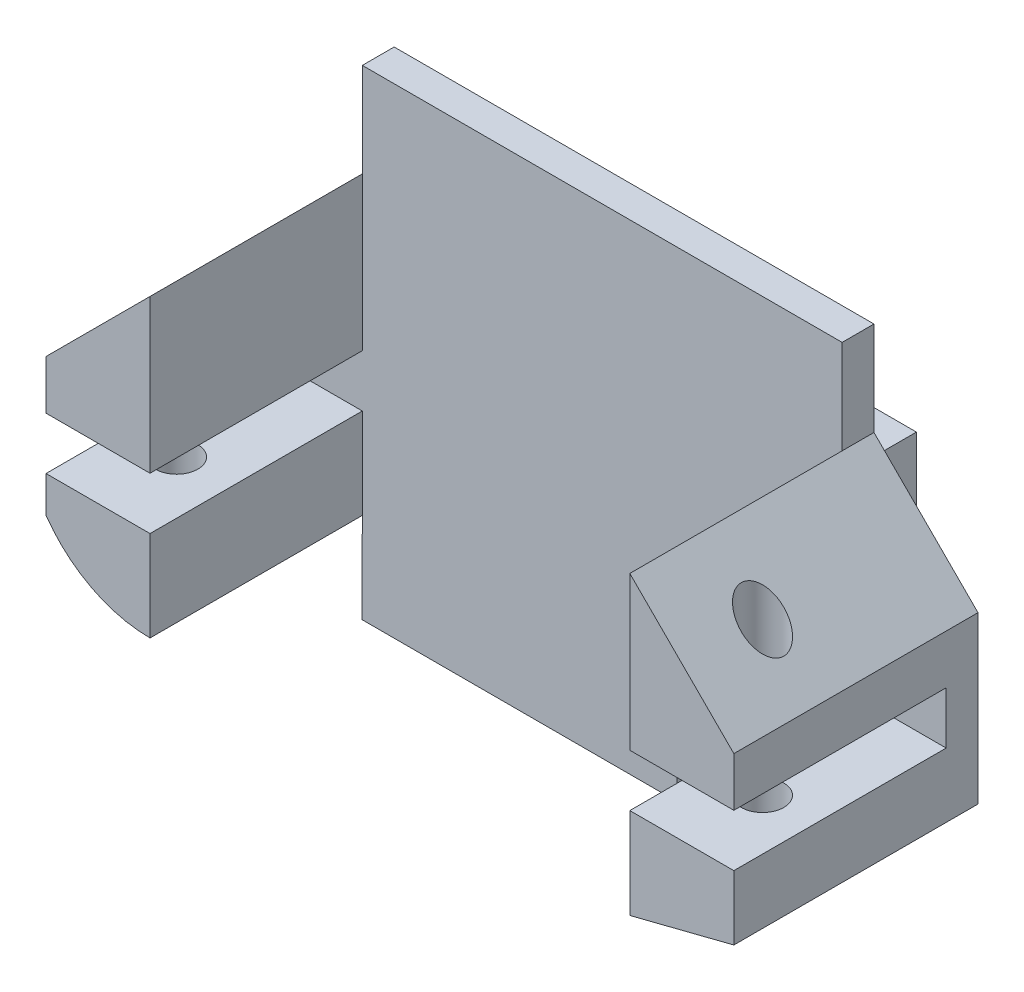
SolidWorks part; units mm, degrees
ref_plane "前视基准面" through (0, 0, 0) normal (0, 0, 1) x (1, 0, 0)
ref_plane "上视基准面" through (0, 0, 0) normal (0, 1, 0) x (1, 0, 0)
ref_plane "右视基准面" through (0, 0, 0) normal (1, 0, 0) x (0, 0, -1)
sketch "草图1" plane through (0, 0, 0) normal (0, 0, 1) x (1, 0, 0)
  line L5 (-16.5627, 3.0348) -> (-16.5627, 29.1923) construction
  line L6 (15.8373, 3.0348) -> (15.8373, 26.0998) construction
  line L8 (-16.5627, -12.8666) -> (15.8373, -12.8666)
  line L9 (-16.5627, -12.8666) -> (-16.5627, 17.1334)
  line L10 (-16.5627, 17.1334) -> (15.8373, 17.1334)
  line L11 (15.8373, -12.8666) -> (15.8373, 17.1334)
extrude "凸台-拉伸1" add sketch "草图1" along normal blind 1.5
sketch "草图2" plane through (0, 0, 1.5) normal (0, 0, 1) x (1, 0, 0)
  line L0 (-16.5627, 17.1334) -> (-16.5627, -12.8666) construction
  line L1 (-16.5627, 3.0348) -> (-11.6627, 3.0348)
  line L2 (-16.5627, 3.0348) -> (-16.5627, -5.4852)
  line L5 (-16.5627, 3.0348) -> (-11.6627, 3.0348) construction
  line L6 (-16.5627, 5.4948) -> (-11.6627, 5.4948)
  line L7 (-11.6627, 5.4948) -> (-16.5627, 5.4948) construction
  line L8 (-11.6627, 5.4948) -> (-11.6627, 12.7081)
  line L9 (-11.6627, 21.7548) -> (-11.6627, 5.4948) construction
  line L11 (-11.6627, 12.7081) -> (-16.5627, 7.8081)
  line L12 (-16.5627, 7.8081) -> (-16.5627, 5.4948)
  line L13 (10.9373, 5.4948) -> (10.9373, 12.7081)
  line L14 (10.9373, 5.4948) -> (10.9373, 21.7548) construction
  line L15 (10.9373, 12.7081) -> (15.8373, 7.8081)
  line L16 (15.8373, -12.8666) -> (15.8373, 17.1334) construction
  line L17 (15.8373, 7.8081) -> (15.8373, 5.4948)
  line L18 (15.8373, 5.4948) -> (10.9373, 5.4948) construction
  line L19 (15.8373, 5.4948) -> (10.9373, 5.4948)
  line L20 (10.9373, 3.0348) -> (15.8373, 3.0348)
  line L21 (10.9373, 3.0348) -> (15.8373, 3.0348) construction
  line L22 (15.8373, 3.0348) -> (15.8373, 0)
  line L23 (15.8373, 0) -> (10.9373, -1.2452)
  line L24 (10.9373, -1.2452) -> (10.9373, 3.0348)
  line L25 (-16.5627, -5.4852) -> (-11.6627, -5.4852)
  line L26 (-11.6627, -5.4852) -> (-11.6627, 3.0348)
extrude "凸台-拉伸2" add sketch "草图2" along normal blind 10
sketch "草图3" plane through (0, 0, 1.5) normal (0, 0, 1) x (1, 0, 0)
  line L0 (-16.5627, 7.8081) -> (-11.6627, 12.7081)
  line L1 (-11.6627, 12.7081) -> (-11.6627, 17.1334)
  line L2 (15.8373, 17.1334) -> (-16.5627, 17.1334) construction
  line L3 (-11.6627, 21.7548) -> (-11.6627, 5.4948) construction
  line L4 (-11.6627, 17.1334) -> (-16.5627, 17.1334)
  line L5 (-16.5627, 17.1334) -> (-16.5627, 7.8081)
  line L6 (15.8373, 7.8081) -> (10.9373, 12.7081)
  line L7 (10.9373, 12.7081) -> (10.9373, 17.1334)
  line L8 (10.9373, 5.4948) -> (10.9373, 21.7548) construction
  line L9 (10.9373, 17.1334) -> (15.8373, 17.1334)
  line L10 (15.8373, 17.1334) -> (15.8373, 7.8081)
  line L11 (-16.5627, -12.8666) -> (-16.5627, -8.702)
  line L12 (-16.5627, -5.4852) -> (-16.5627, -12.8666) construction
  line L13 (-16.5627, -8.702) -> (-16.5627, -5.4852)
  line L14 (-16.5627, -5.4852) -> (3.1573, -5.4852)
  line L15 (3.1573, -5.4852) -> (3.1573, -1.2452)
  line L16 (3.1573, -1.2452) -> (10.9373, -1.2452)
  line L17 (10.9373, -1.2452) -> (15.8373, 0)
  line L18 (15.8373, 0) -> (15.8373, -12.8666)
  line L19 (15.8373, -12.8666) -> (-16.5627, -12.8666)
extrude "切除-拉伸1" cut sketch "草图3" against normal blind 11.5
sketch "草图4" plane through (0, -5.4852, 0) normal (0, -1, 0) x (1, 0, 0)
  circle A0 centre (-14.1627, 7.75) radius 1
  circle A1 centre (13.4373, 7.75) radius 1
  dimension "D1" = 2
  dimension "D2" = 2
extrude "切除-拉伸2" cut sketch "草图4" against normal blind 31.5
sketch "草图5" plane through (0, 0, 11.5) normal (0, 0, 1) x (1, 0, 0)
  line L0 (-11.6627, -5.4852) -> (-11.6627, -1.2252)
  line L1 (-11.6627, -5.4852) -> (-11.6627, 3.0348) construction
  line L2 (-16.5627, 3.0348) -> (-16.5627, -5.4852) construction
  line L3 (-16.5627, 1.3321) -> (-16.5627, -5.4852)
  line L4 (-16.5627, -5.4852) -> (-11.6627, -5.4852)
  arc A0 (-11.6627, -1.2252) -> (-16.5627, 1.3321) centre (-11.6627, 4.7478) cw
extrude "切除-拉伸3" cut sketch "草图5" against normal blind 10
sketch "草图6" plane through (0, 0, 0) normal (0, 0, -1) x (-1, 0, 0)
  line L0 (4.5627, 9.1334) -> (7.4127, 9.1334) construction
  line L1 (7.4127, 5.1334) -> (4.5627, 5.1334) construction
  line L2 (-5.2873, 9.1334) -> (-2.4373, 9.1334) construction
  line L3 (-2.4373, 5.1334) -> (-5.2873, 5.1334) construction
  line L4 (4.5627, 9.1334) -> (7.4127, 9.1334)
  line L5 (7.4127, 5.1334) -> (4.5627, 5.1334)
  line L6 (-5.2873, 9.1334) -> (-2.4373, 9.1334)
  line L7 (-2.4373, 5.1334) -> (-5.2873, 5.1334)
  line L8 (-2.4373, 5.1334) -> (-2.4373, 2.4367)
  line L9 (-2.4373, 2.4367) -> (-10.9373, 2.4367)
  line L10 (-10.9373, 3.0348) -> (-10.9373, -1.2452) construction
  line L11 (-10.9373, 2.4367) -> (-10.9373, 11.7252)
  line L12 (-10.9373, 12.7081) -> (-10.9373, 5.4948) construction
  line L13 (-10.9373, 11.7252) -> (-2.4373, 11.7252)
  line L14 (-2.4373, 11.7252) -> (-2.4373, 9.1334)
  line L15 (4.5627, 5.1334) -> (4.5627, 2.4367)
  line L17 (4.5627, 2.4367) -> (11.6627, 2.4367)
  line L18 (11.6627, -1.2252) -> (11.6627, 3.0348) construction
  line L19 (11.6627, 2.4367) -> (11.6627, 11.7252)
  line L20 (11.6627, 5.4948) -> (11.6627, 12.7081) construction
  line L21 (11.6627, 11.7252) -> (4.5627, 11.7252)
  line L23 (4.5627, 11.7252) -> (4.5627, 9.1334)
  arc A0 (7.4127, 5.1334) -> (7.4127, 9.1334) centre (7.4127, 7.1334) ccw construction
  arc A1 (-5.2873, 9.1334) -> (-5.2873, 5.1334) centre (-5.2873, 7.1334) ccw construction
  arc A2 (7.4127, 5.1334) -> (7.4127, 9.1334) centre (7.4127, 7.1334) ccw
  arc A3 (-5.2873, 9.1334) -> (-5.2873, 5.1334) centre (-5.2873, 7.1334) ccw
extrude "凸台-拉伸3" add sketch "草图6" along normal blind 2
sketch "草图7" plane through (0, 0, 1.5) normal (0, 0, 1) x (1, 0, 0)
  line L0 (-16.5627, 1.3321) -> (-16.5627, -5.4852)
  line L1 (-16.5627, -5.4852) -> (-11.6834, -5.4852)
  line L2 (3.1573, -5.4852) -> (-16.5627, -5.4852) construction
  line L3 (-11.6834, -5.4852) -> (-11.6627, -1.2252)
  arc A0 (-16.5627, 1.3321) -> (-11.6627, -1.2252) centre (-11.6627, 4.7478) ccw construction
  arc A1 (-16.5627, 1.3321) -> (-11.6627, -1.2252) centre (-11.6627, 4.7478) ccw
extrude "切除-拉伸4" cut sketch "草图7" against normal blind 6
sketch "草图8" plane through (0, -1.2452, 0) normal (0, -1, 0) x (1, 0, 0)
  circle A0 centre (13.4373, 7.75) radius 2.25
  circle A1 centre (-14.1627, 7.75) radius 2.25
extrude "切除-拉伸5" cut sketch "草图8" against normal blind 2
